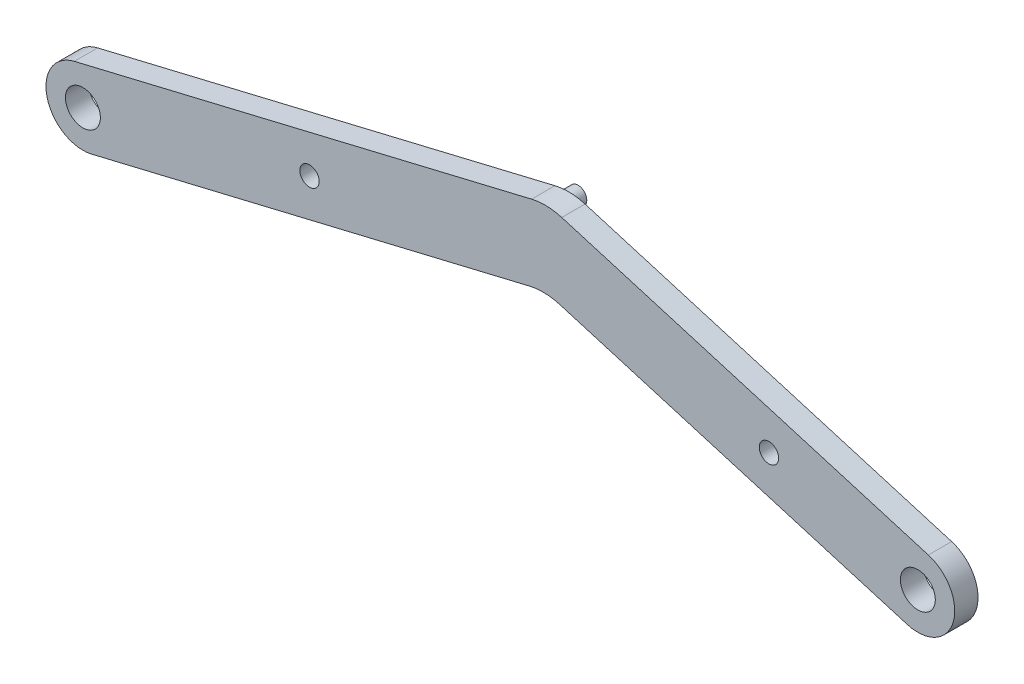
SolidWorks part; units mm, degrees
ref_plane "Alzado" through (0, 0, 0) normal (0, 0, 1) x (1, 0, 0)
ref_plane "Planta" through (0, 0, 0) normal (0, 1, 0) x (1, 0, 0)
ref_plane "Vista lateral" through (0, 0, 0) normal (1, 0, 0) x (0, 0, -1)
sketch "Croquis1" plane through (0, 0, 0) normal (0, 0, 1) x (1, 0, 0)
  line L0 (-214.3946, 25.5184) -> (215.6054, 25.5184) construction
  line L1 (215.6054, 25.5184) -> (-80.5594, 113.5739) construction
  line L2 (24.5175, 102.1545) -> (221.0203, 43.7305)
  line L3 (-214.3946, 25.5184) -> (156.2587, 114.1061) construction
  line L4 (23.4477, 62.8286) -> (210.1906, 7.3063)
  line L5 (-214.3946, 25.5184) -> (-178.7827, 145.2949) construction
  line L6 (-218.8112, 43.9979) -> (24.5175, 102.1545)
  line L7 (-209.9779, 7.0389) -> (23.4477, 62.8286)
  arc A0 (210.1906, 7.3063) -> (221.0203, 43.7305) centre (215.6054, 25.5184) ccw
  arc A1 (-218.8112, 43.9979) -> (-209.9779, 7.0389) centre (-214.3946, 25.5184) ccw
  circle A2 centre (-214.3946, 25.5184) radius 9
  circle A3 centre (215.6054, 25.5184) radius 9
  point P2 (0, 0)
  dimension "D2" = 18
  dimension "D4" = 240
  dimension "D6" = 19
  dimension "D10" = 19
  dimension "D7" = 430
  dimension "D3" = 150
  dimension "D5" = 38
  dimension "D8" = 194.8221
extrude "Saliente-Extruir1" add sketch "Croquis1" along normal blind 12
fillet "Redondeo1" radius 30 2 edges at (24.5175, 102.1545, 6) (23.4477, 62.8286, 6)
sketch "Croquis2" plane through (0, 0, 12) normal (0, 0, 1) x (1, 0, 0)
  line L0 (215.6054, 25.5184) -> (-69.5187, 110.2913) construction
  line L1 (221.0203, 43.7305) -> (32.2226, 99.8636) construction
  line L2 (-214.3946, 25.5184) -> (142.3226, 110.7753) construction
  line L3 (16.6992, 100.2859) -> (-218.8112, 43.9979) construction
  circle A0 centre (138.923, 48.3175) radius 5
  circle A1 centre (215.6054, 25.5184) radius 9 construction
  circle A2 centre (-97.6818, 53.4132) radius 5
  circle A3 centre (-214.3946, 25.5184) radius 9 construction
  dimension "D1" = 10
  dimension "D2" = 80
  dimension "D3" = 10
  dimension "D4" = 120
extrude "Cortar-Extruir1" cut sketch "Croquis2" against normal through all
sketch "Croquis3" plane through (0, 0, 0) normal (0, 0, -1) x (-1, 0, 0)
  line L0 (-16.6992, 100.2859) -> (218.8112, 43.9979) construction
  circle A0 centre (-16.6102, 89.983) radius 4.5
  circle A1 centre (97.6818, 53.4132) radius 5 construction
  dimension "D1" = 9
  dimension "D2" = 120
  dimension "D3" = 10
extrude "Saliente-Extruir2" add sketch "Croquis3" along normal blind 12
ref_plane "Plano1" through (-142.437, -54.428, 331) normal (-0.9413, -0.3377, 0) x (0, 0, 1)
